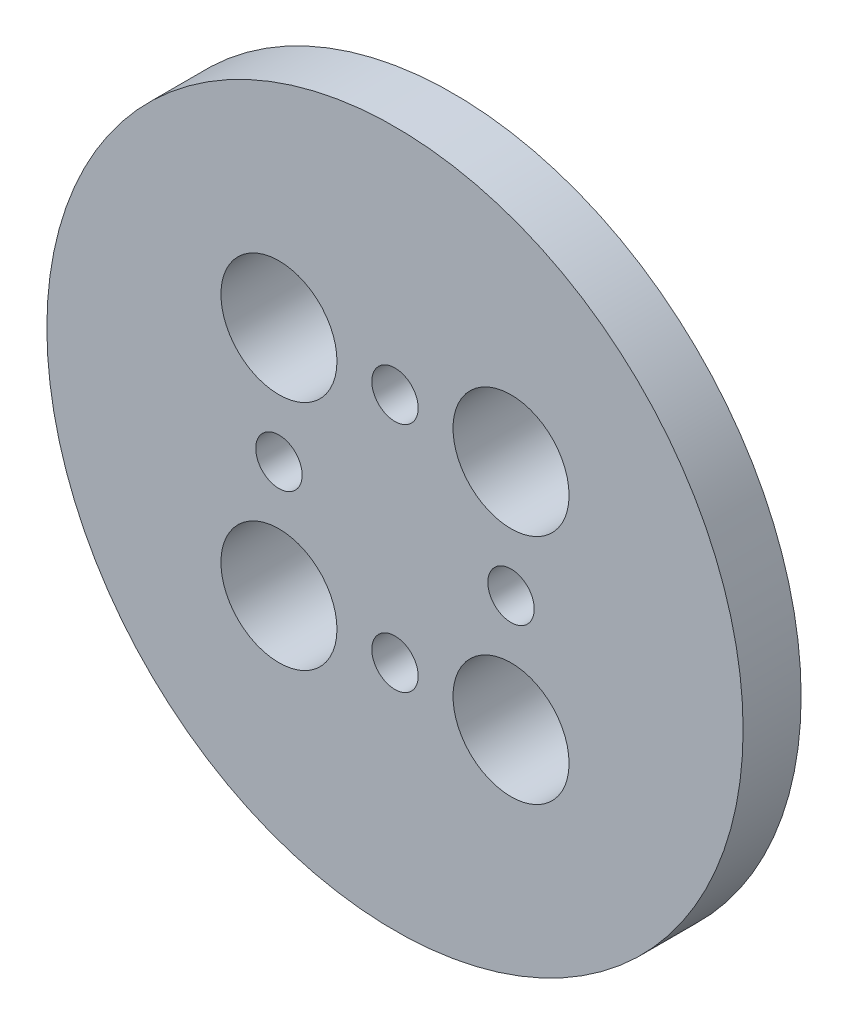
SolidWorks part; units mm, degrees
ref_plane "Front Plane" through (0, 0, 0) normal (0, 0, 1) x (1, 0, 0)
ref_plane "Top Plane" through (0, 0, 0) normal (0, 1, 0) x (1, 0, 0)
ref_plane "Right Plane" through (0, 0, 0) normal (1, 0, 0) x (0, 0, -1)
sketch "Sketch1" plane through (0, 0, 0) normal (0, 0, 1) x (1, 0, 0)
  circle A0 centre (0, 0) radius 15
  dimension "D1" = 30
extrude "body" add sketch "Sketch1" along normal blind 5 contours A0
sketch "Sketch2" plane through (0, 0, 0) normal (0, 0, -1) x (-1, 0, 0)
  circle A0 centre (0, 0) radius 15
  circle A1 centre (0, 0) radius 10
  circle A2 centre (0, 0) radius 15 construction
  dimension "D1" = 5
extrude "slew bearing lip" cut sketch "Sketch2" against normal blind 2.5
sketch "Sketch3" plane through (0, 0, 5) normal (0, 0, 1) x (1, 0, 0)
  circle A0 centre (-5, 5) radius 2.5
  circle A1 centre (5, 5) radius 2.5
  circle A2 centre (5, -5) radius 2.5
  circle A3 centre (-5, -5) radius 2.5
  dimension "D1" = 5
  dimension "D2" = 5
  dimension "D3" = 5
  dimension "D5" = 5
  dimension "D4" = 4
extrude "Cut-Extrude2" cut sketch "Sketch3" against normal through all
sketch "Sketch4" plane through (0, 0, 5) normal (0, 0, 1) x (1, 0, 0)
  circle A0 centre (0, 5) radius 1
  circle A1 centre (5, 0) radius 1
  circle A2 centre (0, -5) radius 1
  circle A3 centre (-5, 0) radius 1
  point P2 (0, 0)
  point P4 (0, 0)
  dimension "D1" = 2
  dimension "D2" = 5
  dimension "D3" = 4
extrude "Cut-Extrude3" cut sketch "Sketch4" against normal through all
